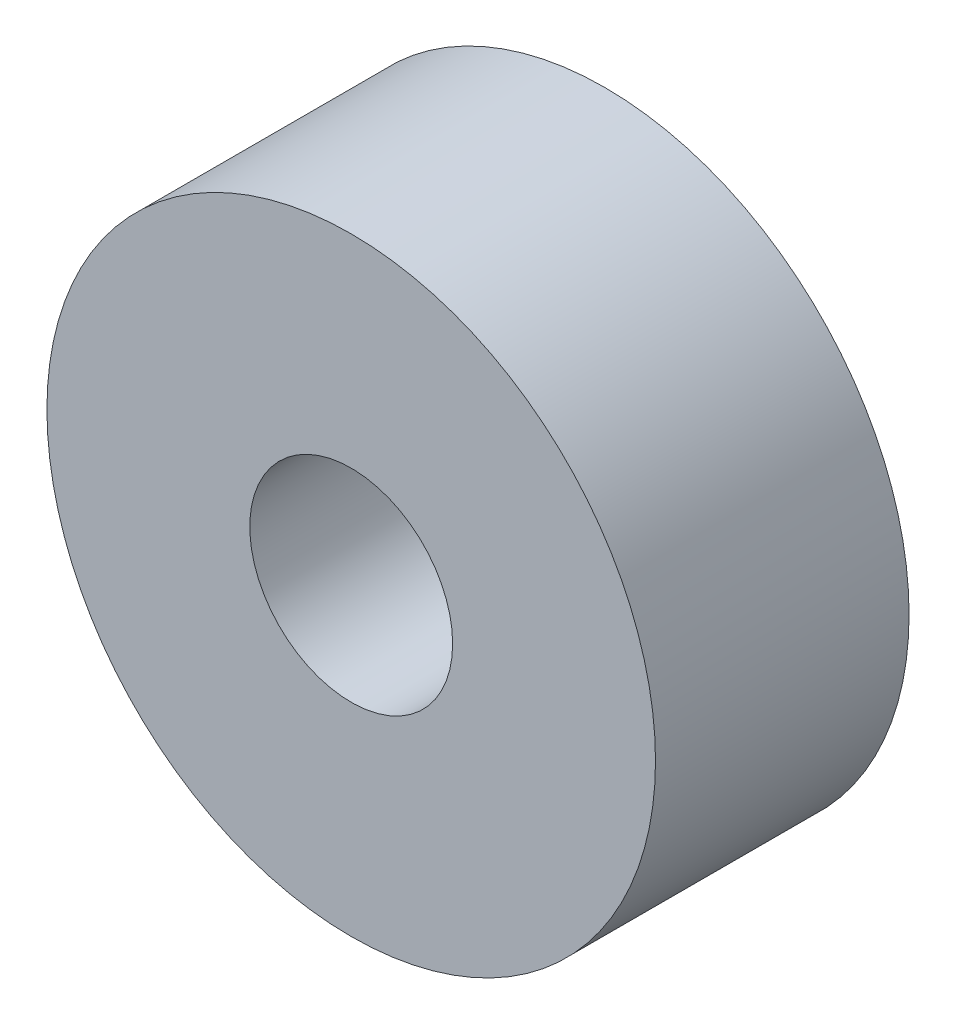
SolidWorks part; units mm, degrees
ref_plane "Front Plane" through (0, 0, 0) normal (1, 0, 0) x (0, 1, 0)
ref_plane "Top Plane" through (0, 0, 0) normal (0, 0, 1) x (0, 1, 0)
ref_plane "Right Plane" through (0, 0, 0) normal (0, 1, 0) x (-1, 0, 0)
sketch "Sketch2" plane through (0, 0, 0) normal (0, 0, 1) x (0, 1, 0)
  circle A0 centre (0, 0) radius 4
  circle A1 centre (0, 0) radius 12
  dimension "D1" = 8
  dimension "D2" = 24
extrude "Boss-Extrude1" add sketch "Sketch2" along normal blind 10
